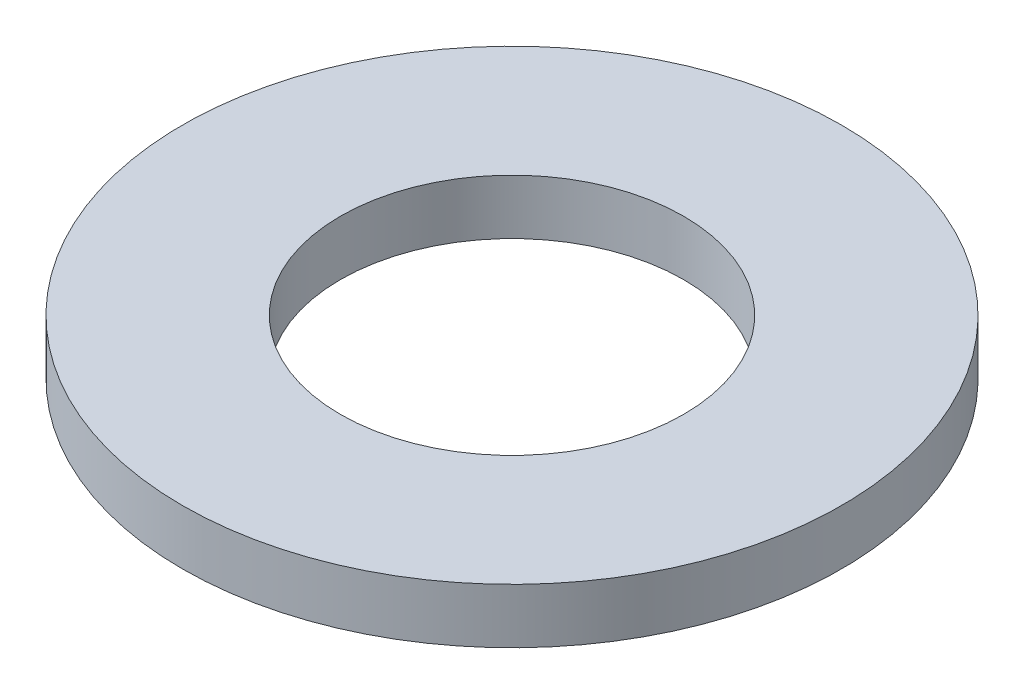
SolidWorks part; units mm, degrees
ref_plane "Front Plane" through (0, 0, 0) normal (1, 0, 0) x (0, 1, 0)
ref_plane "Top Plane" through (0, 0, 0) normal (0, 0, 1) x (0, 1, 0)
ref_plane "Right Plane" through (0, 0, 0) normal (0, 1, 0) x (-1, 0, 0)
sketch "Sketch1" plane through (0, 0, 0) normal (0, 1, 0) x (-1, 0, 0)
  circle A0 centre (0, 0) radius 3.125
  circle A1 centre (0, 0) radius 6
  dimension "D1" = 6.25
  dimension "D2" = 12
extrude "Boss-Extrude1" add sketch "Sketch1" along normal blind 1
